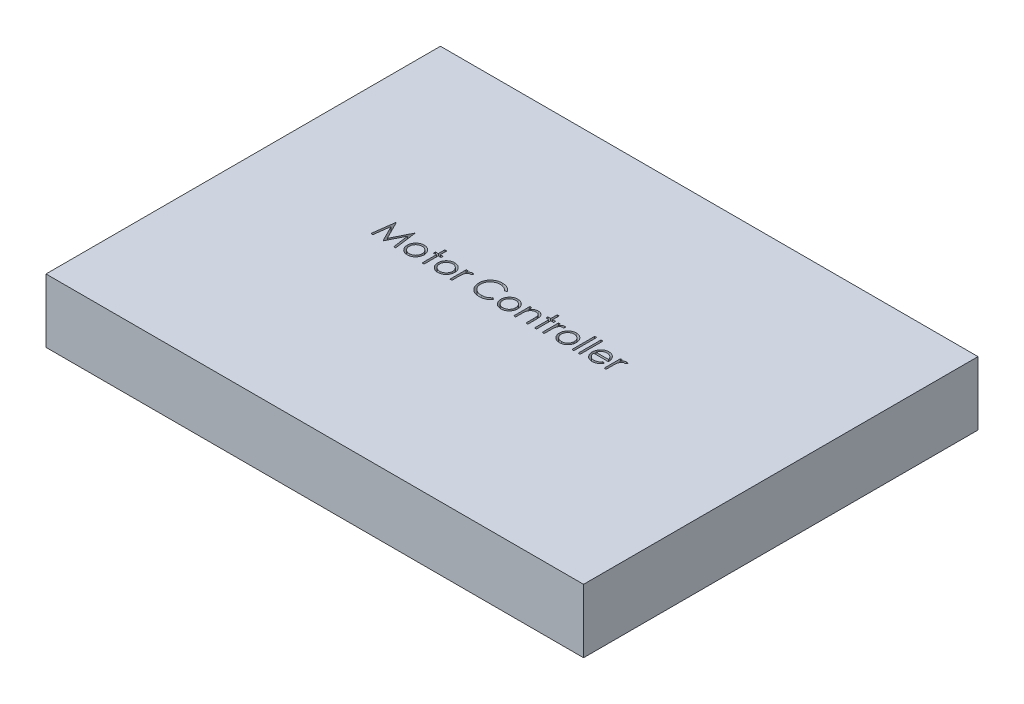
SolidWorks part; units mm, degrees
ref_plane "Front Plane" through (0, 0, 0) normal (0, 0, 1) x (1, 0, 0)
ref_plane "Top Plane" through (0, 0, 0) normal (0, 1, 0) x (1, 0, 0)
ref_plane "Right Plane" through (0, 0, 0) normal (1, 0, 0) x (0, 0, -1)
sketch "Sketch1" plane through (0, 0, 0) normal (0, 1, 0) x (1, 0, 0)
  line L1 (-42.25, -31) -> (42.25, -31)
  line L2 (-42.25, -31) -> (-42.25, 31)
  line L3 (-42.25, 31) -> (42.25, 31)
  line L4 (42.25, -31) -> (42.25, 31)
  line L5 (-42.25, -31) -> (42.25, 31) construction
  line L6 (-42.25, 31) -> (42.25, -31) construction
  point P0 (0, 0)
extrude "Boss-Extrude1" add sketch "Sketch1" along normal blind 10
sketch "Sketch2" plane through (0, 10, 0) normal (0, 1, 0) x (1, 0, 0)
  text T0 "Motor Controller"
extrude "Cut-Extrude1" cut sketch "Sketch2" against normal blind 2.032
